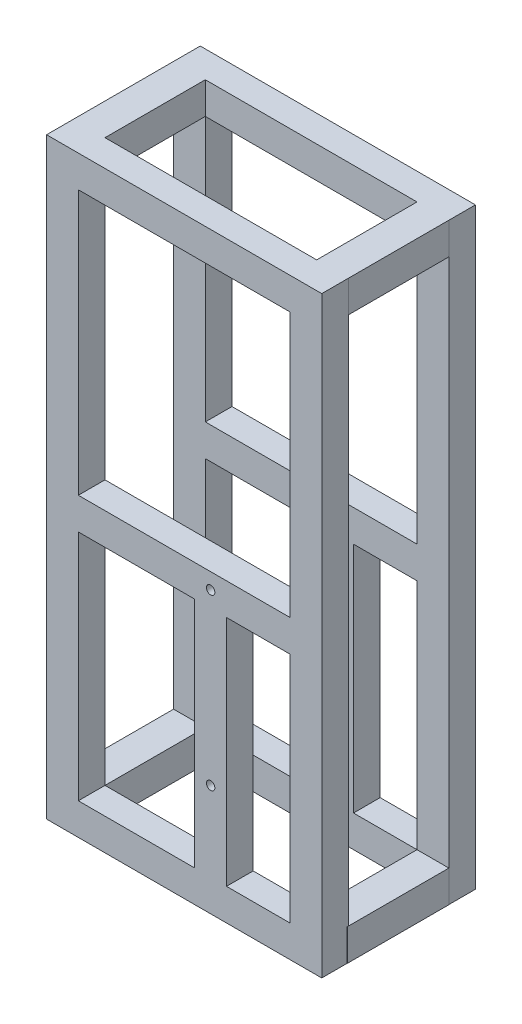
SolidWorks part; units mm, degrees
ref_plane "Plan de face" through (0, 0, 0) normal (0, 0, 1) x (1, 0, 0)
ref_plane "Plan de dessus" through (0, 0, 0) normal (0, 1, 0) x (1, 0, 0)
ref_plane "Plan de droite" through (0, 0, 0) normal (1, 0, 0) x (0, 0, -1)
sketch "Esquisse1" plane through (0, 0, 0) normal (0, 0, 1) x (1, 0, 0)
  line L0 (0, 0) -> (0, 1400)
  line L1 (0, 1400) -> (650, 1400)
  line L2 (650, 1400) -> (650, 0)
  line L3 (650, 0) -> (0, 0)
  line L4 (75, 75) -> (350, 75)
  line L5 (350, 75) -> (350, 625)
  line L6 (350, 625) -> (75, 625)
  line L7 (75, 625) -> (75, 75)
  line L8 (425, 75) -> (425, 625)
  line L9 (425, 75) -> (575, 75)
  line L10 (425, 625) -> (575, 625)
  line L11 (575, 75) -> (575, 625)
  line L12 (75, 1325) -> (575, 1325)
  line L13 (75, 1325) -> (75, 700)
  line L14 (575, 1325) -> (575, 700)
  line L15 (75, 700) -> (575, 700)
  line L16 (0, 576.4266) -> (650, 576.4266) construction
  line L17 (325, 0) -> (325, 700) construction
  dimension "D1" = 75
  dimension "D2" = 75
  dimension "D3" = 75
  dimension "D4" = 650
  dimension "D5" = 1400
  dimension "D6" = 75
  dimension "D7" = 75
  dimension "D8" = 550
  dimension "D9" = 75
  dimension "D10" = 75
  dimension "D11" = 75
  dimension "D12" = 75
  dimension "D13" = 150
extrude "Boss.-Extru.1" add sketch "Esquisse1" along normal blind 63
pattern_linear "Répétition linéaire1" count 2 spacing 300 along (0, 0, 1) of "Boss.-Extru.1"
sketch "Esquisse2" plane through (0, 0, 63) normal (0, 0, 1) x (1, 0, 0)
  line L0 (75, 75) -> (75, 0)
  line L1 (75, 75) -> (0, 75)
  line L2 (75, 0) -> (0, 0)
  line L3 (0, 75) -> (0, 0)
  line L4 (0, 0) -> (650, 0) construction
  line L6 (575, 75) -> (575, 0)
  line L7 (575, 75) -> (650.2866, 75)
  line L8 (575, 0) -> (650.2866, 0)
  line L9 (650.2866, 75) -> (650.2866, 0)
  line L10 (575, 1325) -> (575, 1400)
  line L11 (575, 1325) -> (649.9842, 1325)
  line L12 (575, 1400) -> (649.9842, 1400)
  line L13 (649.9842, 1325) -> (649.9842, 1400)
  line L14 (650, 1400) -> (0, 1400) construction
  line L15 (75, 1325) -> (75, 1400)
  line L16 (75, 1325) -> (0, 1325)
  line L17 (75, 1400) -> (0, 1400)
  line L18 (0, 1325) -> (0, 1400)
extrude "Boss.-Extru.2" add sketch "Esquisse2" along normal blind 240
sketch "Esquisse15" plane through (0, 0, 0) normal (0, 0, -1) x (-1, 0, 0)
  line L0 (-350, 625) -> (-425, 700) construction
  line L1 (-425, 625) -> (-425, 700) construction
  line L2 (-75, 700) -> (-575, 700) construction
  circle A0 centre (-387.5, 662.5) radius 10
  circle A1 centre (-387.5, 262.5) radius 10
  dimension "D1" = 400
extrude "Enlèv. mat.-Extru.4" cut sketch "Esquisse15" against normal through all
